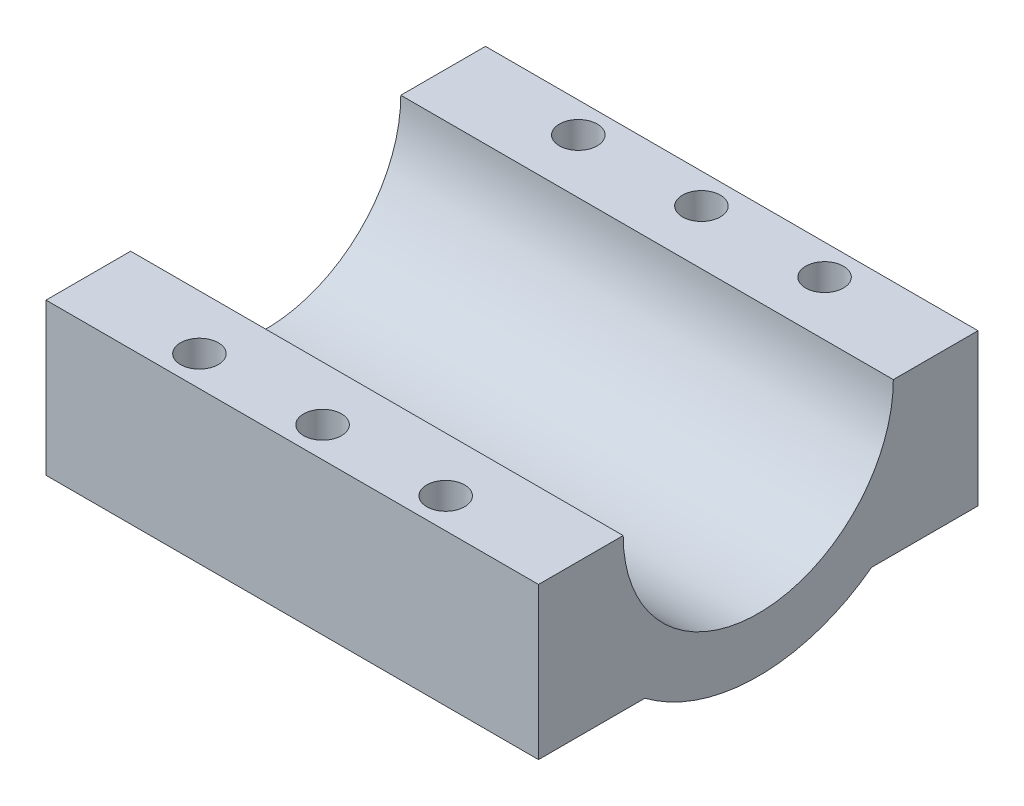
SolidWorks part; units mm, degrees
ref_plane "Front Plane" through (0, 0, 0) normal (0, 0, 1) x (1, 0, 0)
ref_plane "Top Plane" through (0, 0, 0) normal (0, 1, 0) x (1, 0, 0)
ref_plane "Right Plane" through (0, 0, 0) normal (1, 0, 0) x (0, 0, -1)
sketch "Sketch1" plane through (0, 0, 0) normal (0, 1, 0) x (1, 0, 0)
  line L0 (-40.0608, 0) -> (47.511, 0) construction
  line L1 (-32.5, -29) -> (32.5, -29)
  line L2 (-32.5, -29) -> (-32.5, 29)
  line L3 (-32.5, 29) -> (32.5, 29)
  line L4 (32.5, -29) -> (32.5, 29)
  line L5 (-32.5, -29) -> (32.5, 29) construction
  line L6 (-32.5, 29) -> (32.5, -29) construction
  line L7 (-32.5, 25) -> (32.5, 25) construction
  line L8 (-32.5, 18.075) -> (32.5, 18.075) construction
  line L9 (-32.5, -25) -> (32.5, -25) construction
  line L10 (-32.5, -18.075) -> (32.5, -18.075) construction
  line L11 (0, -29) -> (0, 29) construction
  circle A0 centre (-16.25, 25) radius 2.5
  circle A1 centre (16.25, 25) radius 2.5
  circle A2 centre (16.25, -25) radius 2.5
  circle A3 centre (-16.25, -25) radius 2.5
  circle A4 centre (0, 25) radius 2.5
  circle A5 centre (0, -25) radius 2.5
  point P0 (0, 0)
  dimension "D3" = 5
  dimension "D4" = 5
  dimension "D9" = 5
  dimension "D10" = 5
  dimension "D1" = 65
  dimension "D2" = 58
  dimension "D5" = 16.25
  dimension "D6" = 16.25
  dimension "D7" = 18.075
  dimension "D8" = 4
extrude "Boss-Extrude1" add sketch "Sketch1" along normal blind 25
sketch "Sketch2" plane through (32.5, 0, 0) normal (1, 0, 0) x (0, 0, -1)
  line L0 (-29, 25) -> (29, 25) construction
  line L1 (-29, 25) -> (-17.825, 25) construction
  line L3 (-29, 0) -> (29, 0) construction
  line L4 (29, 25) -> (17.825, 25) construction
  line L6 (-14.9638, 4.9729) -> (-29, 4.9729)
  line L7 (-29, 25) -> (-29, 0) construction
  line L11 (29, 25) -> (29, 0) construction
  line L12 (29, 4.9729) -> (14.9638, 4.9729)
  line L13 (0, -12.8013) -> (0, 49.7133) construction
  line L14 (-29, 4.9729) -> (-29, -6.794)
  line L15 (-29, -6.794) -> (29, -6.794)
  line L16 (29, -6.794) -> (29, 4.9729)
  circle A0 centre (0, 25) radius 17.825
  arc A1 (-14.9638, 4.9729) -> (14.9638, 4.9729) centre (0, 25) ccw
  dimension "D2" = 35.65
  dimension "D1" = 0
  dimension "D3" = 11.7669
extrude "Cut-Extrude1" cut sketch "Sketch2" against normal through all
sketch "Sketch3" plane through (0, 4.9729, 0) normal (0, -1, 0) x (1, 0, 0)
  circle A0 centre (-16.25, -25) radius 6
  circle A1 centre (0, -25) radius 6
  circle A2 centre (16.25, -25) radius 6
  circle A3 centre (16.25, 25) radius 6
  circle A4 centre (0, 25) radius 6
  circle A5 centre (-16.25, 25) radius 6
  dimension "D1" = 12
  dimension "D2" = 12
  dimension "D3" = 12
  dimension "D4" = 12
  dimension "D5" = 12
  dimension "D6" = 12
